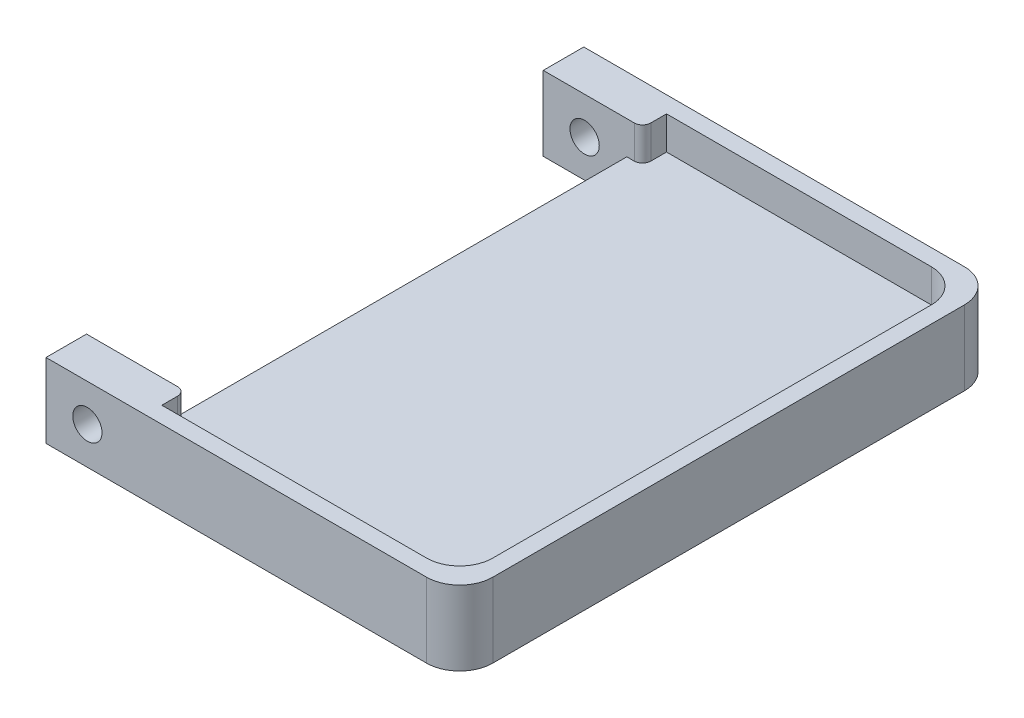
SolidWorks part; units mm, degrees
ref_plane "Front Plane" through (0, 0, 0) normal (0, 0, 1) x (1, 0, 0)
ref_plane "Top Plane" through (0, 0, 0) normal (0, 1, 0) x (1, 0, 0)
ref_plane "Right Plane" through (0, 0, 0) normal (1, 0, 0) x (0, 0, -1)
sketch "Sketch1" plane through (0, 0, 0) normal (0, 0, 1) x (1, 0, 0)
  line L1 (0, 0) -> (63.5, 0)
  line L2 (0, 0) -> (0, 11.43)
  line L3 (0, 11.43) -> (63.5, 11.43)
  line L4 (63.5, 0) -> (63.5, 11.43)
  dimension "D1" = 11.43
  dimension "D2" = 63.5
extrude "Boss-Extrude1" add sketch "Sketch1" along normal blind 82.55
sketch "Sketch2" plane through (0, 11.43, 0) normal (0, 1, 0) x (1, 0, 0)
  line L0 (63.5, -82.55) -> (63.5, 0) construction
  line L1 (15.24, -2.54) -> (60.96, -2.54)
  line L2 (15.24, -2.54) -> (15.24, -80.01)
  line L3 (15.24, -80.01) -> (60.96, -80.01)
  line L4 (60.96, -2.54) -> (60.96, -80.01)
  line L5 (63.5, 0) -> (0, 0) construction
  line L6 (63.5, -82.55) -> (0, -82.55) construction
  dimension "D1" = 2.54
  dimension "D2" = 2.54
  dimension "D3" = 2.54
  dimension "D4" = 45.72
extrude "Cut-Extrude1" cut sketch "Sketch2" against normal blind 5.08
sketch "Sketch3" plane through (0, 11.43, 0) normal (0, 1, 0) x (1, 0, 0)
  line L0 (13.335, -6.223) -> (13.335, -76.327)
  line L1 (0, 0) -> (13.335, 0)
  line L2 (0, 0) -> (0, -6.223)
  line L3 (0, -6.223) -> (13.335, -6.223)
  line L4 (13.335, 0) -> (13.335, -6.223)
  line L5 (0, -6.223) -> (0, -76.327)
  line L6 (0, -82.55) -> (13.335, -82.55)
  line L7 (0, -82.55) -> (0, -76.327)
  line L8 (0, -76.327) -> (13.335, -76.327)
  line L9 (13.335, -82.55) -> (13.335, -76.327)
  line M10 (0, 0) -> (0, -82.55)
  dimension "D1" = 6.223
  dimension "D2" = 13.335
  dimension "D3" = 6.223
  dimension "D4" = 13.335
extrude "Cut-Extrude2" cut sketch "Sketch3" against normal through all contours L8 L0 L3 M10
sketch "Sketch4" plane through (0, 11.43, 0) normal (0, 1, 0) x (1, 0, 0)
  line L0 (15.24, -2.54) -> (15.24, -80.01) construction
  line L1 (13.335, -6.223) -> (15.24, -6.223)
  line L2 (13.335, -6.223) -> (13.335, -76.327)
  line L3 (13.335, -76.327) -> (15.24, -76.327)
  line L4 (15.24, -6.223) -> (15.24, -76.327)
  dimension "D1" = 70.104
extrude "Cut-Extrude3" cut sketch "Sketch4" against normal blind 5.08
fillet "Fillet1" radius 5.08 2 edges at (60.96, 8.89, 80.01) (60.96, 8.89, 2.54)
fillet "Fillet2" radius 5.08 2 edges at (63.5, 5.715, 0) (63.5, 5.715, 82.55)
fillet "Fillet3" radius 1.27 2 edges at (15.24, 8.89, 76.327) (15.24, 8.89, 6.223)
sketch "Sketch5" plane through (0, 0, 82.55) normal (0, 0, 1) x (1, 0, 0)
  line L0 (58.42, 11.43) -> (0, 11.43) construction
  line L1 (0, 11.43) -> (0, 0) construction
  circle A0 centre (6.35, 5.715) radius 2.2479
  dimension "D3" = 4.4958
  dimension "D1" = 5.715
  dimension "D2" = 6.35
extrude "Cut-Extrude4" cut sketch "Sketch5" against normal through all contours A0
sketch "Sketch6" plane through (13.335, 0, 0) normal (-1, 0, 0) x (0, 0, 1)
  line L1 (6.223, 6.35) -> (76.327, 6.35)
  line L2 (6.223, 6.35) -> (6.223, 0)
  line L3 (6.223, 0) -> (76.327, 0)
  line L4 (76.327, 6.35) -> (76.327, 0)
extrude "Boss-Extrude2" add sketch "Sketch6" along normal blind 0.508
